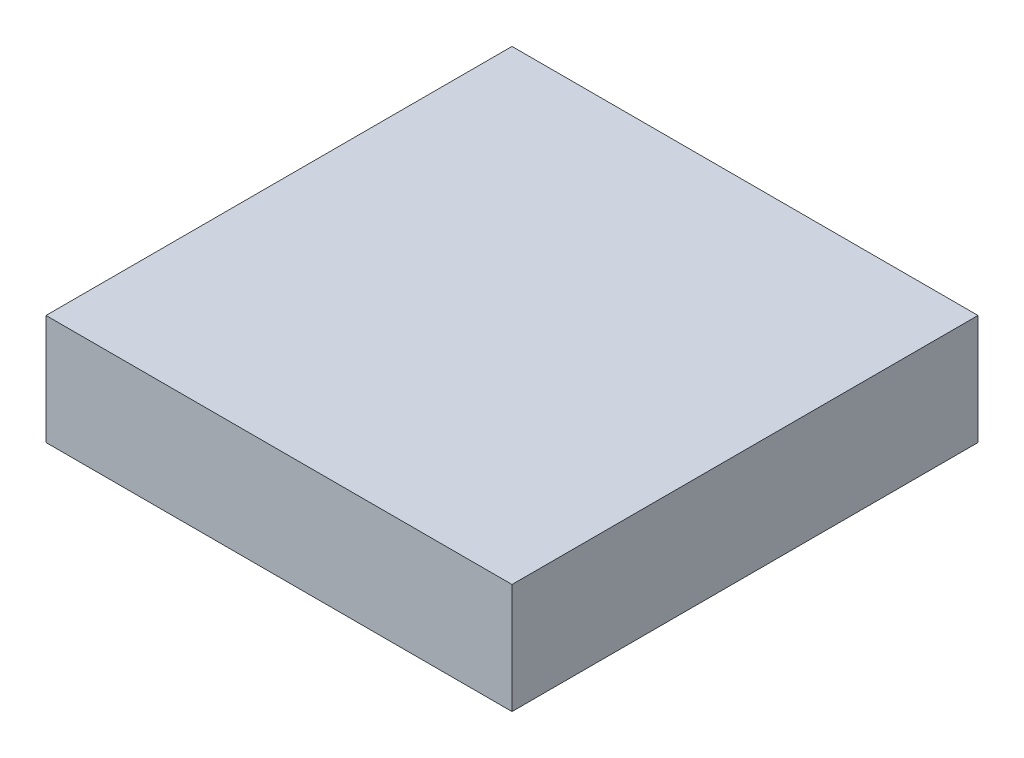
SolidWorks part; units mm, degrees
ref_plane "Front" through (0, 0, 0) normal (0, 0, 1) x (1, 0, 0)
ref_plane "Top" through (0, 0, 0) normal (0, 1, 0) x (1, 0, 0)
ref_plane "Right" through (0, 0, 0) normal (1, 0, 0) x (0, 0, -1)
sketch "Croquis1" plane through (0, 0, 0) normal (0, 1, 0) x (1, 0, 0)
  line L1 (0, 0) -> (12.7, 0)
  line L2 (0, 0) -> (0, 12.7)
  line L3 (0, 12.7) -> (12.7, 12.7)
  line L4 (12.7, 0) -> (12.7, 12.7)
  dimension "D1" = 12.7
  dimension "D2" = 12.7
extrude "Saliente-Extruir1" add sketch "Croquis1" along normal blind 3
